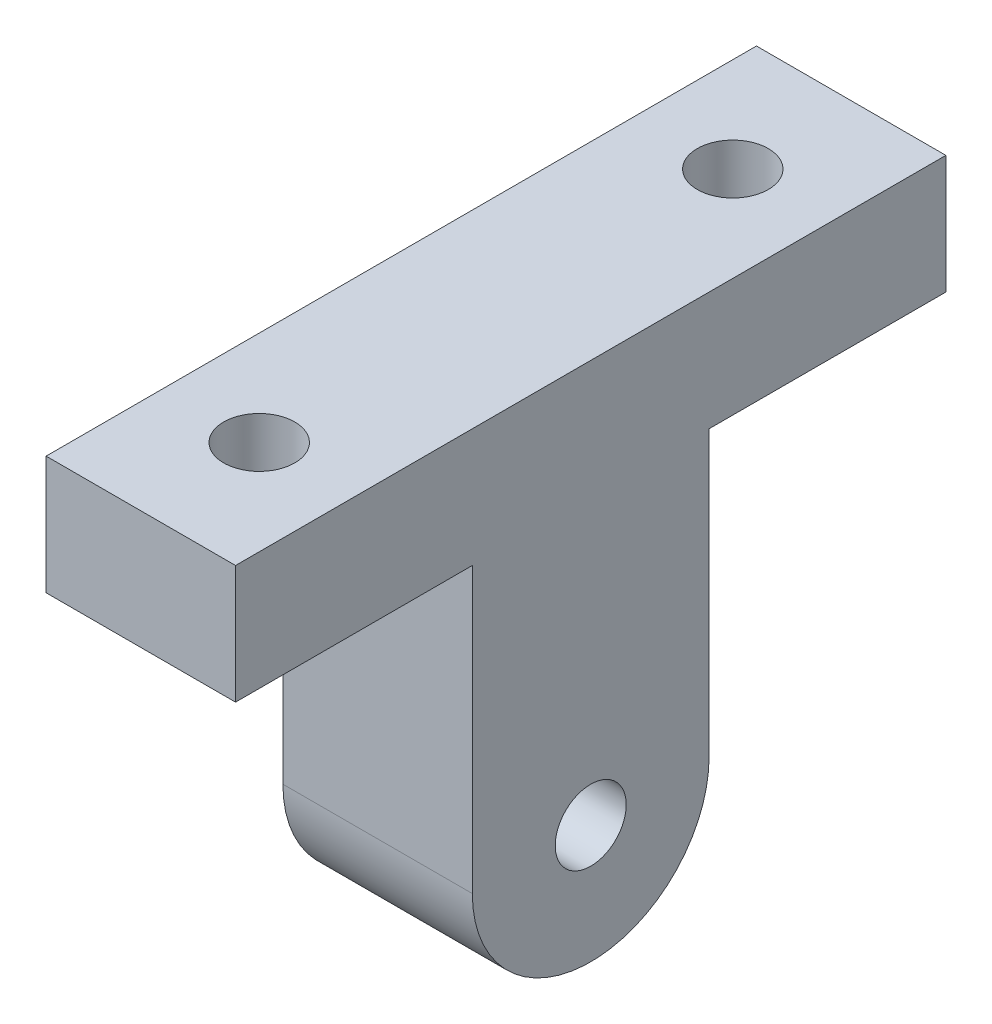
SolidWorks part; units mm, degrees
ref_plane "前视基准面" through (0, 0, 0) normal (0, 0, 1) x (1, 0, 0)
ref_plane "上视基准面" through (0, 0, 0) normal (0, 1, 0) x (1, 0, 0)
ref_plane "右视基准面" through (0, 0, 0) normal (1, 0, 0) x (0, 0, -1)
sketch "草图1" plane through (0, 0, 0) normal (1, 0, 0) x (0, 0, -1)
  line L0 (5, 12) -> (15, 12)
  line L2 (-5, 0) -> (-5, 12)
  line L4 (5, 0) -> (5, 12)
  line L5 (-15, 17) -> (15, 17)
  line L6 (-15, 17) -> (-15, 12)
  line L7 (-15, 12) -> (-5, 12)
  line L8 (15, 17) -> (15, 12)
  arc A0 (-5, 0) -> (5, 0) centre (0, 0) ccw
  circle A1 centre (0, 0) radius 1.5
  dimension "D1" = 10
  dimension "D6" = 3
  dimension "D2" = 17
  dimension "D3" = 5
  dimension "D4" = 30
  dimension "D5" = 15
extrude "凸台-拉伸1" add sketch "草图1" along normal mid plane 8
sketch "草图2" plane through (0, 12, 0) normal (0, -1, 0) x (1, 0, 0)
  line L0 (-4, 0) -> (4, 0) construction
  line L1 (-4, 5) -> (-4, -5) construction
  line L2 (4, -5) -> (4, 5) construction
  line L3 (4, 15) -> (-4, 15) construction
  line L4 (4, 15) -> (4, 5) construction
  circle A0 centre (0, 10) radius 1.5
  circle A1 centre (0, -10) radius 1.5
  dimension "D1" = 3
  dimension "D2" = 5
  dimension "D3" = 4
extrude "切除-拉伸1" cut sketch "草图2" against normal up to next
